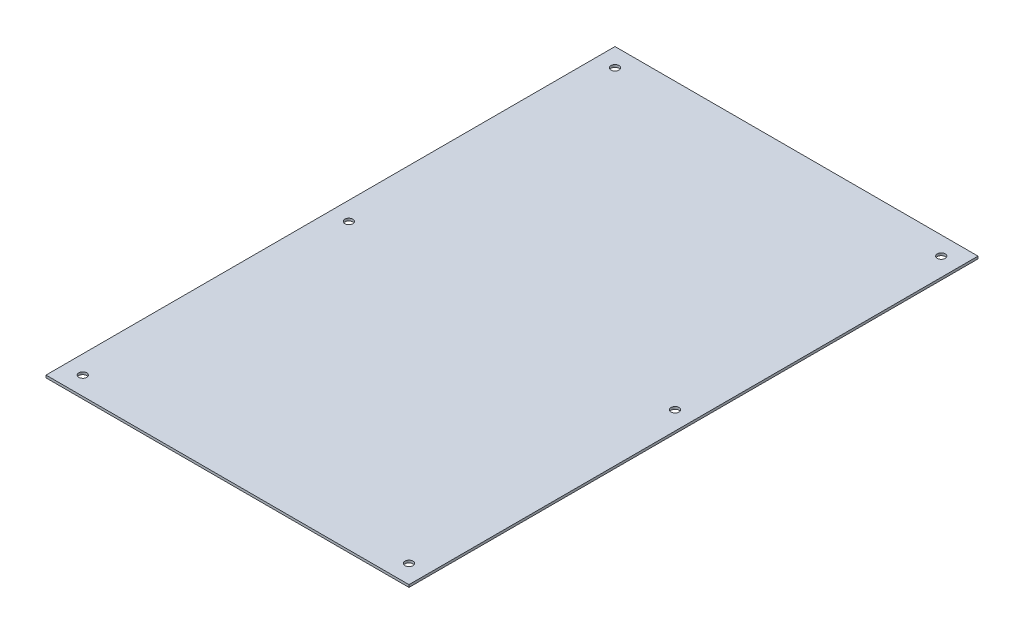
SolidWorks part; units mm, degrees
ref_plane "Front Plane" through (0, 0, 0) normal (0, 0, 1) x (1, 0, 0)
ref_plane "Top Plane" through (0, 0, 0) normal (0, 1, 0) x (1, 0, 0)
ref_plane "Right Plane" through (0, 0, 0) normal (1, 0, 0) x (0, 0, -1)
sketch "Sketch1" plane through (0, 0, 0) normal (0, 1, 0) x (1, 0, 0)
  line L1 (-148, -232) -> (148, -232)
  line L2 (-148, -232) -> (-148, 232)
  line L3 (-148, 232) -> (148, 232)
  line L4 (148, -232) -> (148, 232)
  line L5 (-148, -232) -> (148, 232) construction
  line L6 (-148, 232) -> (148, -232) construction
  point P0 (0, 0)
  dimension "D1" = 464
  dimension "D2" = 296
extrude "Boss-Extrude1" add sketch "Sketch1" along normal blind 2
sketch "Sketch2" plane through (0, 2, 0) normal (0, 1, 0) x (1, 0, 0)
  line L0 (148, 232) -> (-148, 232) construction
  line L1 (-148, 232) -> (-148, -232) construction
  line L2 (0, 0) -> (0, 232) construction
  line L3 (0, 0) -> (148, 0) construction
  line L4 (148, -232) -> (148, 232) construction
  circle A0 centre (-133, 217) radius 3.25
  circle A1 centre (133, 217) radius 3.25
  circle A2 centre (-133, -217) radius 3.25
  circle A3 centre (133, -217) radius 3.25
  circle A4 centre (133, 0) radius 3.25
  circle A5 centre (-133, 0) radius 3.25
  dimension "D1" = 6.5
  dimension "D4" = 6.5
  dimension "D2" = 15
  dimension "D3" = 15
  dimension "D5" = 15
extrude "Cut-Extrude1" cut sketch "Sketch2" against normal blind 2
